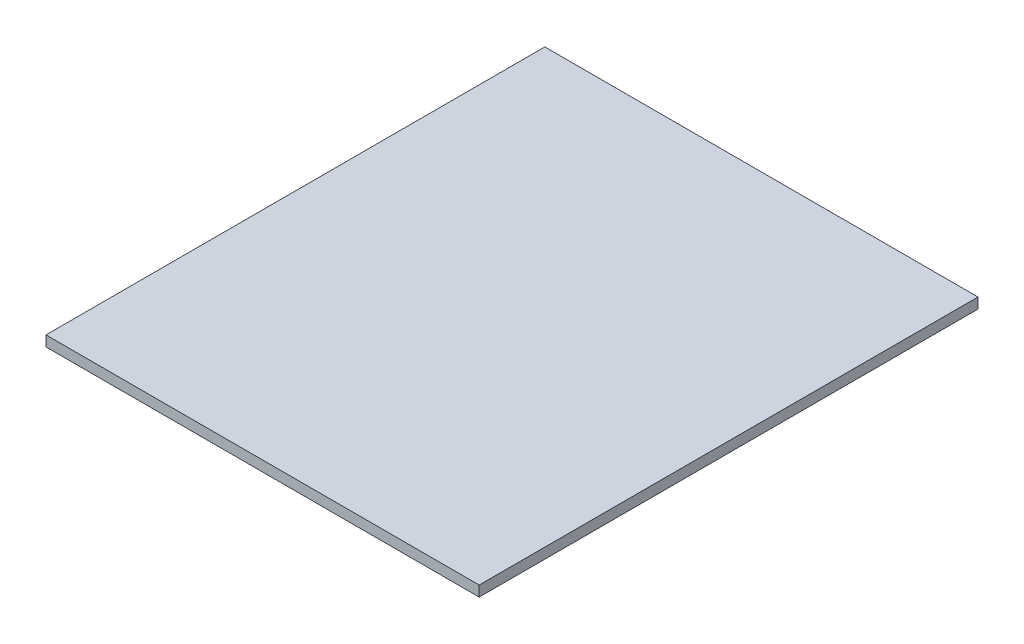
SolidWorks part; units mm, degrees
ref_plane "Front Plane" through (0, 0, 0) normal (0, 0, 1) x (1, 0, 0)
ref_plane "Top Plane" through (0, 0, 0) normal (0, 1, 0) x (1, 0, 0)
ref_plane "Right Plane" through (0, 0, 0) normal (1, 0, 0) x (0, 0, -1)
sketch "Sketch1" plane through (0, 0, 0) normal (0, 1, 0) x (1, 0, 0)
  line L0 (-859.6759, -965.078) -> (816.7241, -965.078)
  line L1 (-859.6759, -965.078) -> (-859.6759, 965.322)
  line L2 (-859.6759, 965.322) -> (816.7241, 965.322)
  line L3 (816.7241, -965.078) -> (816.7241, 965.322)
  dimension "D1" = 1930.4
  dimension "D2" = 1676.4
extrude "Boss-Extrude1" add sketch "Sketch1" along normal blind 40.4812
